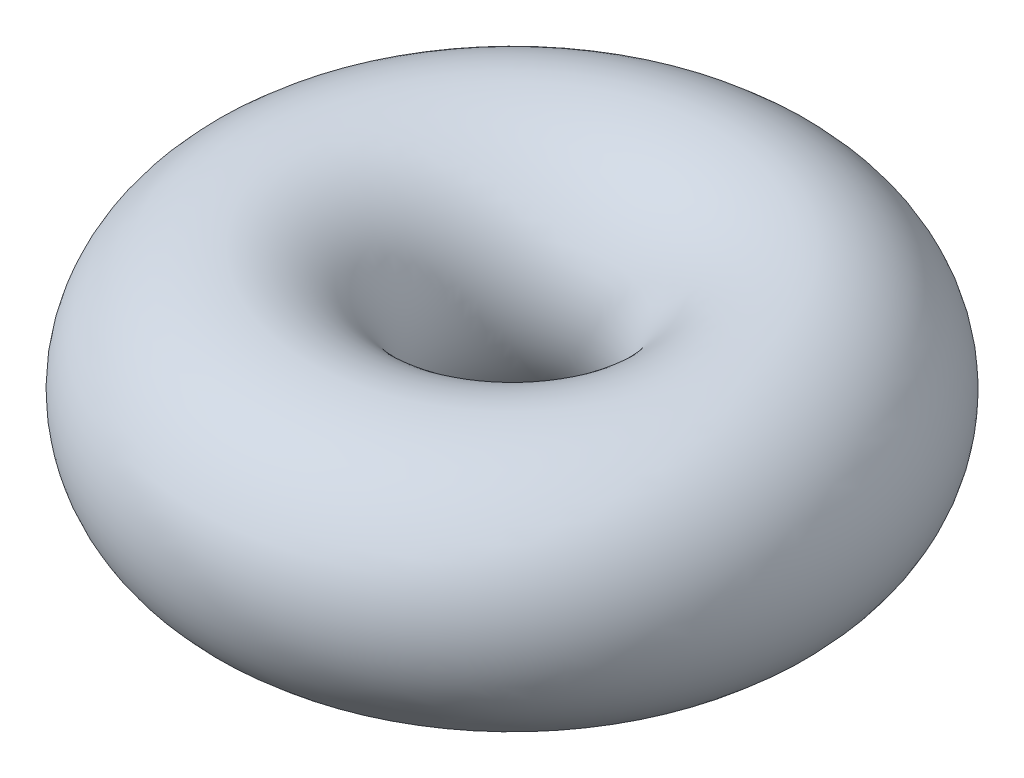
SolidWorks part; units mm, degrees
ref_plane "Front Plane" through (0, 0, 0) normal (0, 0, 1) x (1, 0, 0)
ref_plane "Top Plane" through (0, 0, 0) normal (0, 1, 0) x (1, 0, 0)
ref_plane "Right Plane" through (0, 0, 0) normal (1, 0, 0) x (0, 0, -1)
sketch "Sketch2" plane through (0, 0, 0) normal (0, 0, 1) x (1, 0, 0)
  line L0 (0, 4.9966) -> (0, -6.2527) construction
  circle A0 centre (2.5, 0) radius 1.5
  dimension "D1" = 2.5
  dimension "D2" = 3
  dimension "D3" = 0
revolve "Revolve1" add sketch "Sketch2" angle 360 about L0
sketch "Sketch3" plane through (0, 0, 0) normal (0, 1, 0) x (1, 0, 0)
  circle A0 centre (0, 0) radius 3.56 construction
  dimension "D1" = 7.12
ref_plane "Plane1" through (0, 1.5, 0) normal (0, 1, 0) x (1, 0, 0)
sketch "Sketch4" plane through (0, 1.5, 0) normal (0, 1, 0) x (1, 0, 0)
  circle A0 centre (0, 0) radius 2.5 construction
  dimension "D1" = 5
ref_plane "Plane2" through (0, -1.5, 0) normal (0, 1, 0) x (1, 0, 0)
sketch "Sketch5" plane through (0, -1.5, 0) normal (0, 1, 0) x (1, 0, 0)
  circle A0 centre (0, 0) radius 2.5 construction
  dimension "D1" = 5
